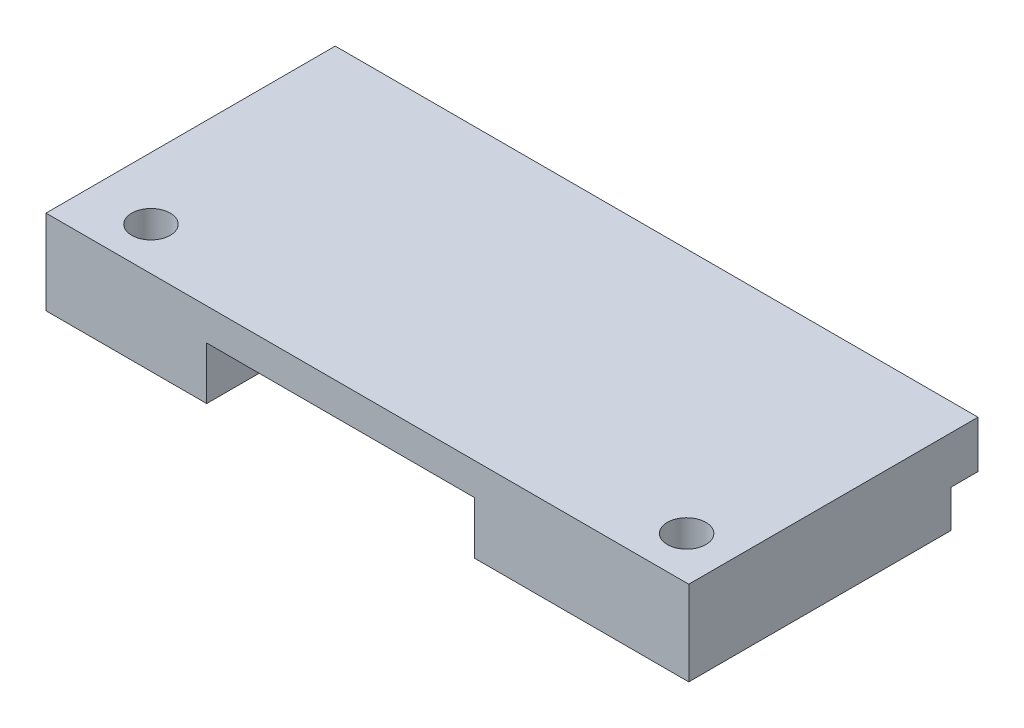
SolidWorks part; units mm, degrees
ref_plane "Płaszczyzna przednia" through (0, 0, 0) normal (0, 0, 1) x (1, 0, 0)
ref_plane "Płaszczyzna górna" through (0, 0, 0) normal (0, 1, 0) x (1, 0, 0)
ref_plane "Płaszczyzna prawa" through (0, 0, 0) normal (1, 0, 0) x (0, 0, -1)
sketch "Sketch1" plane through (0, 0, 0) normal (0, 1, 0) x (1, 0, 0)
  line L1 (-30, -1.25) -> (30, -1.25)
  line L2 (-30, -1.25) -> (-30, 1.25)
  line L3 (-30, 1.25) -> (30, 1.25)
  line L4 (30, -1.25) -> (30, 1.25)
  line L5 (-30, -1.25) -> (30, 1.25) construction
  line L6 (-30, 1.25) -> (30, -1.25) construction
  point P0 (0, 0)
  dimension "D1" = 2.5
  dimension "D2" = 60
extrude "Boss-Extrude1" add sketch "Sketch1" along normal blind 2.5
sketch "Sketch2" plane through (0, 2.5, 0) normal (0, 1, 0) x (1, 0, 0)
  line L0 (30, -1.25) -> (30, 1.25) construction
  line L1 (-30, -1.25) -> (30, -1.25)
  line L2 (-30, -1.25) -> (-30, 3.75)
  line L3 (-30, 3.75) -> (30, 3.75)
  line L4 (30, -1.25) -> (30, 3.75)
  line L9 (30, 1.25) -> (-30, 1.25) construction
  dimension "D1" = 2.5
extrude "Boss-Extrude2" add sketch "Sketch2" along normal blind 3
sketch "Sketch5" plane through (0, 0, 1.25) normal (0, 0, 1) x (1, 0, 0)
  line L4 (-30, 0) -> (30, 0)
  line L5 (30, 0) -> (30, 5.5)
  line L6 (30, 5.5) -> (-30, 5.5)
  line L7 (-30, 5.5) -> (-30, 0)
  line L8 (-30, 0) -> (30, 0)
  line L9 (30, 0) -> (30, 5.5)
  line L10 (30, 5.5) -> (-30, 5.5)
  line L11 (-30, 5.5) -> (-30, 0)
  dimension "D1" = 0
extrude "Boss-Extrude4" add sketch "Sketch5" along normal blind 22
sketch "Sketch6" plane through (0, 5.5, 0) normal (0, 1, 0) x (1, 0, 0)
  line L4 (-30, 3.75) -> (-30, -23.25)
  line L5 (-30, -23.25) -> (30, -23.25)
  line L6 (30, -23.25) -> (30, 3.75)
  line L7 (30, 3.75) -> (-30, 3.75)
  line L8 (-30, 3.75) -> (-30, -23.25)
  line L9 (-30, -23.25) -> (30, -23.25)
  line L10 (30, -23.25) -> (30, 3.75)
  line L11 (30, 3.75) -> (-30, 3.75)
  dimension "D1" = 0
extrude "Boss-Extrude5" add sketch "Sketch6" along normal blind 2.4
hole_wizard "Ø3.6 (3.6) Diameter Hole1" positions "Sketch7" profile "Sketch8" hole size "Ø3.6" standard "DIN" end condition through all
sketch "Sketch7" plane through (0, 7.9, 0) normal (0, 1, 0) x (1, 0, 0)
  line L1 (30, -23.25) -> (30, 3.75) construction
  line L2 (-30, -23.25) -> (30, -23.25) construction
  line L3 (25.8, -19.25) -> (-24.2, -19.25)
  point P0 (-24.2, -19.25)
  point P2 (25.8, -19.25)
  dimension "D1" = 50
  dimension "D2" = 4
  dimension "D3" = 4.2
sketch "Sketch8" plane through (-24.2, 7.9, 19.25) normal (1, 0, 0) x (0, 0, 1)
  line L0 (0, 0) -> (0, 7.9)
  line L1 (0, 7.9) -> (1.8, 7.9)
  line L2 (1.8, 7.9) -> (1.8, 0)
  line L5 (1.8, 0) -> (0, 0)
  line L11 (0, -6.35) -> (0, 107.95) construction
  dimension "Thru Hole Dia." = 3.6
  dimension "Thru Hole Depth" = 7.9
sketch "Sketch9" plane through (0, 0, -3.75) normal (0, 0, -1) x (-1, 0, 0)
  line L1 (-10, 4.9) -> (15, 4.9)
  line L2 (-10, 4.9) -> (-10, -4.7096)
  line L3 (-10, -4.7096) -> (15, -4.7096)
  line L4 (15, 4.9) -> (15, -4.7096)
  line L5 (30, 7.9) -> (30, 2.5) construction
  line L7 (-30, 7.9) -> (30, 7.9) construction
  dimension "D1" = 25
  dimension "D2" = 15
  dimension "D3" = 3
extrude "Cut-Extrude1" cut sketch "Sketch9" against normal through all
sketch "Sketch10" plane through (0, 0, -1.25) normal (0, 0, -1) x (-1, 0, 0)
  line L0 (30, 7.9) -> (30, 2.5) construction
  line L1 (-30, 0) -> (30, 0)
  line L2 (-30, 0) -> (-30, 3.5)
  line L3 (-30, 3.5) -> (30, 3.5)
  line L4 (30, 0) -> (30, 3.5)
  dimension "D1" = 3.5
extrude "Cut-Extrude2" cut sketch "Sketch10" along normal through all
